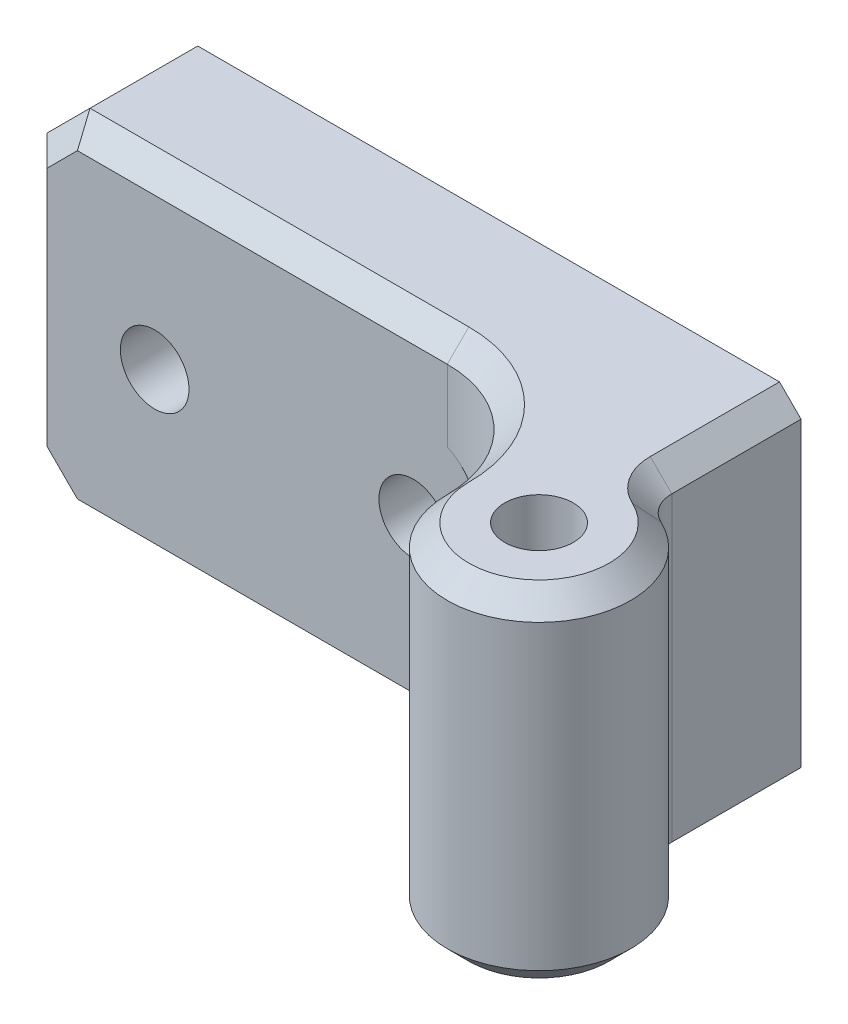
SolidWorks part; units mm, degrees
material "PET"
ref_plane "Front Plane" through (0, 0, 0) normal (0, 0, 1) x (1, 0, 0)
ref_plane "Top Plane" through (0, 0, 0) normal (0, 1, 0) x (1, 0, 0)
ref_plane "Right Plane" through (0, 0, 0) normal (1, 0, 0) x (0, 0, -1)
sketch "Sketch1" plane through (0, 0, 0) normal (0, 0, 1) x (1, 0, 0)
  line L0 (-38.1, 942.7052) -> (-38.1, 427.513) construction
  line L1 (-38.1, 710.9302) -> (9.525, 710.9302)
  line L2 (-38.1, 710.9302) -> (-38.1, 685.5302)
  line L3 (-38.1, 685.5302) -> (9.525, 685.5302)
  line L4 (9.525, 710.9302) -> (9.525, 685.5302)
  line L5 (-169.45, 710.9302) -> (-12.7, 710.9302) construction
  dimension "D1" = 47.625
  dimension "D2" = 25.4
extrude "Boss-Extrude1" add sketch "Sketch1" along normal blind 9.525
sketch "Sketch2" plane through (0, 710.9302, 0) normal (0, -1, 0) x (-1, 0, 0)
  circle A0 centre (-8.0615, -17.8438) radius 6.7575
  arc A1 (-7.1211, -24.5355) -> (-4.4806, -12.1131) centre (-8.0615, -17.8438) ccw construction
extrude "Boss-Extrude2" add sketch "Sketch2" along normal up to surface (25.4 mm away) separate body up to face at (-14.2875, 685.5302, 4.7625)
sketch "Sketch3" plane through (0, 685.5302, 0) normal (0, -1, 0) x (1, 0, 0)
  line L0 (9.525, 9.525) -> (9.525, 0) construction
  line L1 (-38.1, 9.525) -> (9.525, 9.525) construction
  line L2 (9.525, 9.525) -> (-7.0148, 9.525)
  arc A0 (9.525, 9.525) -> (10.9232, 11.7221) centre (11.9503, 9.525) cw
  circle A1 centre (8.0615, 17.8438) radius 6.7575 construction
  arc A2 (1.304, 17.8438) -> (-7.0148, 9.525) centre (-7.0148, 17.8438) cw
  circle A5 centre (8.0615, 17.8438) radius 6.7575
  arc A6 (1.304, 17.8438) -> (10.9232, 11.7221) centre (8.0615, 17.8438) ccw
  point P15 (8.0615, 17.8438)
  dimension "D1" = 0
extrude "Boss-Extrude3" add sketch "Sketch3" against normal up to surface (25.4 mm away) up to face at (-14.2875, 710.9302, 4.7625)
hole_wizard "#8 (0.199) Diameter Hole1" positions "Sketch4" profile "Sketch5" hole size "#8" standard "ANSI Inch" end condition up to next
sketch "Sketch4" plane through (0, 710.9302, 0) normal (0, 1, 0) x (1, 0, 0)
  point P0 (8.0615, -17.8438)
sketch "Sketch5" plane through (8.0615, 710.9302, 17.8438) normal (1, 0, 0) x (0, 0, 1)
  line L0 (0, 0) -> (0, 25.4)
  line L1 (0, 25.4) -> (2.5273, 25.4)
  line L2 (2.5273, 25.4) -> (2.5273, 0)
  line L5 (2.5273, 0) -> (0, 0)
  line L11 (0, -6.35) -> (0, 107.95) construction
  dimension "Thru Hole Dia." = 5.0546
  dimension "Thru Hole Depth" = 25.4
chamfer "Chamfer1" distance 3.175 angle 45 2 edges at (-38.1, 685.5302, 4.7625) (-38.1, 710.9302, 4.7625)
chamfer "Chamfer2" distance 1.5875 angle 45 13 edges at (9.525, 685.5302, 4.7625) (9.525, 710.9302, 4.7625) (9.9042, 710.9302, 10.8271) (9.9042, 685.5302, 10.8271) (11.6896, 685.5302, 23.5447) (11.6896, 710.9302, 23.5447) (-1.1325, 710.9302, 11.9615) (-1.1325, 685.5302, 11.9615) (-20.9699, 685.5302, 9.525) (-36.5125, 687.1177, 9.525) (-38.1, 698.2302, 9.525) (-20.9699, 710.9302, 9.525) (-36.5125, 709.3427, 9.525)
ref_plane "Plane4" through (0, 698.2302, 0) normal (0, 1, 0) x (1, 0, 0)
hole_wizard "Hole1" [suppressed] positions "Sketch6" profile "Sketch7" legacy
sketch "Sketch6" plane through (0, 710.9302, 0) normal (0, 1, 0) x (1, 0, 0)
  point P0 (7.8099, -17.8438)
sketch "Sketch7" plane through (7.8099, 710.9302, 17.8438) normal (1, 0, 0) x (0, 0, 1)
  line L0 (0, 0) -> (0, 4.699)
  line L1 (0, 4.699) -> (2.8702, 4.699)
  line L2 (2.8702, 4.699) -> (2.9972, 0)
  line L3 (2.9972, 0) -> (0, 0)
  line L4 (0, 110) -> (0, -10) construction
  dimension "Minor Diameter" = 5.7404
  dimension "Depth" = 4.699
  dimension "Major Diameter" = 5.9944
mirror "Mirror1" [suppressed] about plane through (0, 698.2302, 0) normal (0, 1, 0)
mirror "Mirror2" about plane through (0, 698.2302, 0) normal (0, 1, 0) of "#8 (0.199) Diameter Hole1"
hole_wizard "#8 (0.199) Diameter Hole2" positions "Sketch9" profile "Sketch10" hole size "#8" standard "ANSI Inch" end condition through all
sketch "Sketch9" plane through (0, 0, 0) normal (0, 0, -1) x (-1, 0, 0)
  line L0 (38.1, 698.2302) -> (-9.525, 698.2302) construction
  line L1 (38.1, 707.7552) -> (38.1, 688.7052) construction
  line L2 (-9.525, 687.1177) -> (-9.525, 709.3427) construction
  point P9 (28.575, 698.2302)
  point P11 (9.525, 698.2302)
  dimension "D1" = 9.525
  dimension "D2" = 19.05
sketch "Sketch10" plane through (-9.525, 698.2302, 0) normal (1, 0, 0) x (0, 1, 0)
  line L0 (0, 0) -> (0, 24.6013)
  line L1 (0, 24.6013) -> (2.5273, 24.6013)
  line L2 (2.5273, 24.6013) -> (2.5273, 0)
  line L5 (2.5273, 0) -> (0, 0)
  line L11 (0, -6.35) -> (0, 107.95) construction
  dimension "Thru Hole Dia." = 5.0546
  dimension "Thru Hole Depth" = 24.6013
sketch "Sketch11" plane through (0, 0, 9.525) normal (0, 0, 1) x (1, 0, 0)
  circle A0 centre (-9.525, 698.2302) radius 6.35
  dimension "D1" = 12.7
extrude "Cut-Extrude1" cut sketch "Sketch11" along normal up to next
